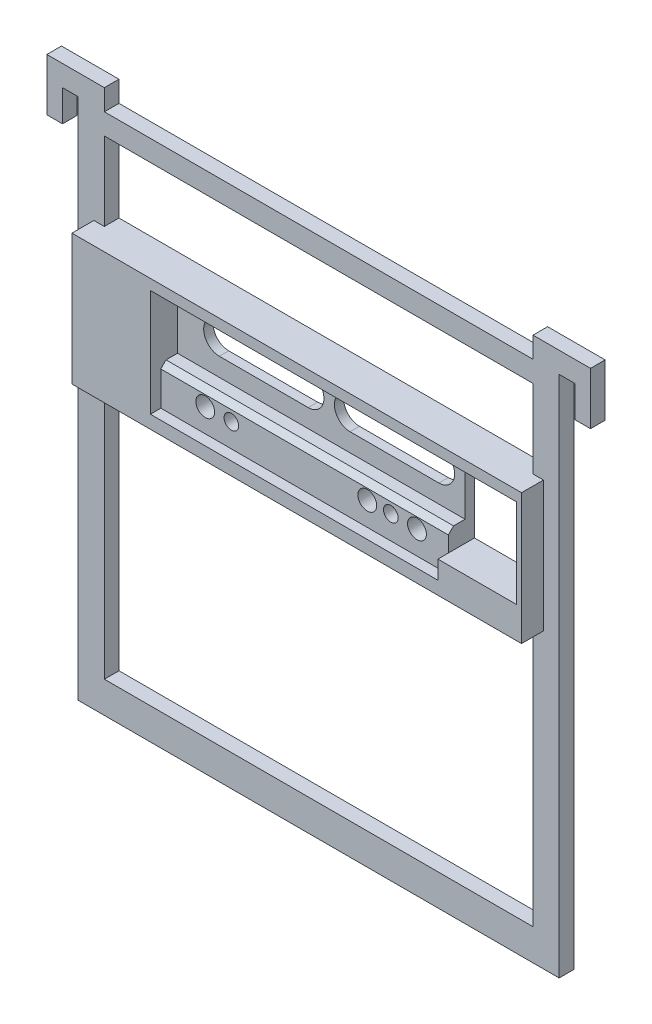
SolidWorks part; units mm, degrees
ref_plane "前视基准面" through (0, 0, 0) normal (0, 0, 1) x (1, 0, 0)
ref_plane "上视基准面" through (0, 0, 0) normal (0, 1, 0) x (1, 0, 0)
ref_plane "右视基准面" through (0, 0, 0) normal (1, 0, 0) x (0, 0, -1)
other "Configuration Table"
sketch "草图1" plane through (0, 0, 0) normal (0, 0, 1) x (1, 0, 0)
  line L1 (0, 0) -> (86, 0)
  line L2 (0, 0) -> (0, 25)
  line L3 (0, 25) -> (86, 25)
  line L4 (86, 0) -> (86, 25)
  dimension "D1" = 86
  dimension "D2" = 25
extrude "凸台-拉伸1" add sketch "草图1" along normal blind 7
sketch "草图2" plane through (0, 0, 7) normal (0, 0, 1) x (1, 0, 0)
  line L0 (86, 0) -> (86, 25) construction
  line L1 (70, 6) -> (85, 6)
  line L2 (70, 6) -> (70, 23)
  line L3 (70, 23) -> (85, 23)
  line L4 (85, 6) -> (85, 23)
  line L5 (0, 0) -> (86, 0) construction
  dimension "D1" = 15
  dimension "D2" = 17
  dimension "D3" = 1
  dimension "D4" = 6
extrude "切除-拉伸1" cut sketch "草图2" against normal through all
sketch "草图3" plane through (0, 0, 7) normal (0, 0, 1) x (1, 0, 0)
  line L1 (70, 23) -> (15, 23)
  line L2 (70, 23) -> (70, 10)
  line L3 (70, 10) -> (15, 10)
  line L4 (15, 23) -> (15, 10)
  dimension "D1" = 55
  dimension "D2" = 13
extrude "切除-拉伸2" cut sketch "草图3" against normal blind 5.2
sketch "草图4" plane through (0, 0, 7) normal (0, 0, 1) x (1, 0, 0)
  line L0 (15, 23) -> (15, 10) construction
  line L1 (70, 10) -> (15, 10)
  line L2 (70, 10) -> (70, 2.5)
  line L3 (70, 2.5) -> (15, 2.5)
  line L4 (15, 10) -> (15, 2.5)
  dimension "D1" = 7.5
extrude "切除-拉伸3" cut sketch "草图4" against normal blind 2
sketch "草图5" plane through (0, 0, 5) normal (0, 0, 1) x (1, 0, 0)
  line L0 (70, 6) -> (70, 10) construction
  line L1 (15, 2.5) -> (70, 2.5) construction
  circle A0 centre (64, 7) radius 1.8
  circle A1 centre (54.5, 7) radius 1.8
  circle A2 centre (23.5, 7) radius 1.8
  dimension "D1" = 3.6
  dimension "D2" = 6
  dimension "D3" = 9.5
  dimension "D4" = 31
  dimension "D5" = 4.5
extrude "切除-拉伸4" cut sketch "草图5" against normal through all
sketch "草图6" plane through (0, 0, 5) normal (0, 0, 1) x (1, 0, 0)
  line L0 (70, 6) -> (70, 10) construction
  line L2 (15, 2.5) -> (70, 2.5) construction
  circle A0 centre (59, 7) radius 1.4
  circle A1 centre (28.5, 7) radius 1.4
  dimension "D1" = 2.8
  dimension "D2" = 41.5
  dimension "D3" = 11
  dimension "D4" = 4.5
extrude "切除-拉伸5" cut sketch "草图6" against normal through all
sketch "草图7" plane through (0, 0, 1.8) normal (0, 0, 1) x (1, 0, 0)
  line L0 (23, 16.5) -> (40, 16.5) construction
  line L1 (23, 19.5) -> (40, 19.5)
  line L2 (23, 13.5) -> (40, 13.5)
  line L3 (48, 16.5) -> (65, 16.5) construction
  line L4 (48, 19.5) -> (65, 19.5)
  line L5 (48, 13.5) -> (65, 13.5)
  line L6 (70, 10) -> (70, 23) construction
  arc A0 (23, 19.5) -> (23, 13.5) centre (23, 16.5) ccw
  arc A1 (40, 13.5) -> (40, 19.5) centre (40, 16.5) ccw
  arc A2 (48, 19.5) -> (48, 13.5) centre (48, 16.5) ccw
  arc A3 (65, 13.5) -> (65, 19.5) centre (65, 16.5) ccw
  point P2 (31.5, 16.5)
  point P7 (56.5, 16.5)
  point P17 (70, 16.5)
  dimension "D4" = 3
  dimension "D5" = 3
  dimension "D1" = 8
  dimension "D2" = 17
  dimension "D3" = 17
  dimension "D6" = 5
extrude "切除-拉伸6" cut sketch "草图7" against normal through all
chamfer "倒角1" distance 1 angle 45 1 edges at (42.5, 10, 5)
sketch "草图8" plane through (0, 0, 0) normal (0, 0, -1) x (-1, 0, 0)
  line L0 (-86, 0) -> (-86, 25) construction
  line L15 (-95, 38) -> (-92, 38)
  line L34 (-92, 38) -> (-92, 44)
  line L59 (-86, 0) -> (0, 0)
  line L60 (0, 0) -> (0, 25)
  line L61 (0, 25) -> (-2, 25)
  line L62 (-92, 44) -> (-89, 44)
  line L69 (-89, 44) -> (-89, -56)
  line L70 (-89, -56) -> (3, -56)
  line L71 (3, -56) -> (3, 44)
  line L72 (3, 44) -> (6, 44)
  line L73 (6, 44) -> (6, 38)
  line L74 (6, 38) -> (9, 38)
  line L75 (9, 38) -> (9, 48)
  line L76 (9, 48) -> (-2, 48)
  line L77 (-2, 48) -> (-2, 44)
  line L78 (-2, 44) -> (-84, 44)
  line L79 (-84, 44) -> (-84, 48)
  line L80 (-84, 48) -> (-95, 48)
  line L81 (-95, 48) -> (-95, 38)
  line L82 (0, 0) -> (-86, 0) construction
  line L83 (-86, 25) -> (0, 25) construction
  line L84 (0, 25) -> (0, 0) construction
  line L85 (-86, 25) -> (-86, 0)
  line L86 (-84, 25) -> (-84, 40)
  line L87 (-84, -2) -> (-2, -2)
  line L88 (-84, -2) -> (-84, -50)
  line L89 (-84, -50) -> (-2, -50)
  line L90 (-2, -2) -> (-2, -50)
  line L91 (-84, 40) -> (-2, 40)
  line L92 (-2, 40) -> (-2, 25)
  line L93 (-84, 25) -> (-86, 25)
  dimension "D1" = 56
  dimension "D2" = 19
  dimension "D3" = 3
  dimension "D4" = 3
  dimension "D5" = 5
  dimension "D6" = 5
  dimension "D7" = 3
  dimension "D8" = 3
  dimension "D9" = 3
  dimension "D10" = 3
  dimension "D11" = 4
  dimension "D12" = 10
  dimension "D13" = 4
  dimension "D14" = 2
  dimension "D15" = 6
extrude "凸台-拉伸2" add sketch "草图8" against normal blind 2.8
